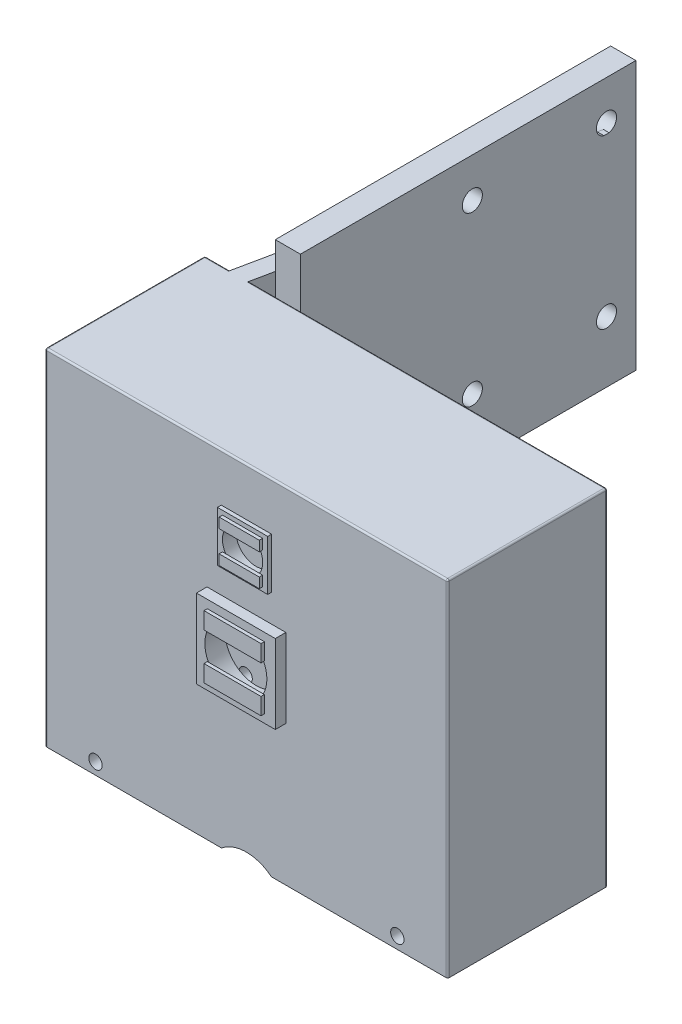
SolidWorks part; units mm, degrees
ref_plane "Front Plane" through (0, 0, 0) normal (0, 0, 1) x (1, 0, 0)
ref_plane "Top Plane" through (0, 0, 0) normal (0, 1, 0) x (1, 0, 0)
ref_plane "Right Plane" through (0, 0, 0) normal (1, 0, 0) x (0, 0, -1)
sketch "Sketch1" plane through (0, 0, 0) normal (1, 0, 0) x (0, 0, -1)
  line L1 (0, 0) -> (95.2, 0)
  line L2 (0, 0) -> (0, 205.7)
  line L3 (0, 205.7) -> (95.2, 205.7)
  line L4 (95.2, 0) -> (95.2, 205.7)
  dimension "D1" = 205.7
  dimension "D2" = 95.2
extrude "Boss-Extrude1" add sketch "Sketch1" against normal blind 240
sketch "Sketch2" plane through (0, 0, 0) normal (0, -1, 0) x (1, 0, 0)
  line L0 (0, 0) -> (0, -95.2) construction
  line L1 (-234.3, -5.7) -> (-5.7, -5.7)
  line L2 (-234.3, -5.7) -> (-234.3, -89.5)
  line L3 (-234.3, -89.5) -> (-5.7, -89.5)
  line L4 (-5.7, -5.7) -> (-5.7, -89.5)
  line L5 (-240, 0) -> (0, 0) construction
  line L6 (-240, 0) -> (-240, -95.2) construction
  line L7 (-240, -95.2) -> (0, -95.2) construction
  dimension "D1" = 5.7
  dimension "D2" = 5.7
  dimension "D3" = 5.7
  dimension "D4" = 5.7
extrude "Cut-Extrude1" cut sketch "Sketch2" against normal blind 194.3
fillet "Fillet1" radius 1 8 edges at (-240, 102.85, 0) (-240, 205.7, -47.6) (-240, 102.85, -95.2) (0, 102.85, -95.2) (-120, 205.7, -95.2) (-120, 205.7, 0) (0, 205.7, -47.6) (0, 102.85, 0)
sketch "Sketch3" plane through (0, 0, 0) normal (0, 0, 1) x (1, 0, 0)
  line L0 (-239, 0) -> (-1, 0) construction
  line L1 (0, 204.7) -> (0, 0) construction
  circle A0 centre (-120, 107) radius 18.5
  dimension "D1" = 107
  dimension "D2" = 120
  dimension "D3" = 37
extrude "Cut-Extrude2" cut sketch "Sketch3" against normal through all
sketch "Sketch4" plane through (0, 0, 0) normal (0, 0, 1) x (1, 0, 0)
  line L5 (-143.5, 130.5) -> (-96.5, 130.5)
  line L6 (-143.5, 130.5) -> (-143.5, 83.5)
  line L7 (-143.5, 83.5) -> (-96.5, 83.5)
  line L8 (-96.5, 130.5) -> (-96.5, 83.5)
  circle A0 centre (-120, 107) radius 18.5 construction
  dimension "D1" = 23.5
  dimension "D2" = 23.5
  dimension "D3" = 23.5
  dimension "D4" = 23.5
extrude "Boss-Extrude2" add sketch "Sketch4" along normal blind 6.3
sketch "Sketch6" plane through (0, 0, -95.2) normal (0, 0, -1) x (-1, 0, 0)
  line L1 (96.5, 130.5) -> (143.5, 130.5)
  line L2 (96.5, 130.5) -> (96.5, 83.5)
  line L3 (96.5, 83.5) -> (143.5, 83.5)
  line L4 (143.5, 130.5) -> (143.5, 83.5)
  circle A0 centre (120, 107) radius 18.5 construction
  circle A2 centre (120, 107) radius 18.5 construction
  dimension "D1" = 23.5
  dimension "D4" = 23.5
  dimension "D3" = 23.5
  dimension "D2" = 23.5
extrude "Boss-Extrude3" add sketch "Sketch6" along normal blind 6.3
sketch "Sketch7" plane through (0, 0, 0) normal (0, 0, 1) x (1, 0, 0)
  circle A0 centre (-120, 107) radius 18.5
  dimension "D3" = 37
extrude "Cut-Extrude3" cut sketch "Sketch7" against normal through all both and the other way through all
sketch "Sketch8" plane through (0, 0, 0) normal (0, 0, 1) x (1, 0, 0)
  line L6 (-239, 0) -> (-1, 0) construction
  circle A0 centre (-120, -18.2) radius 23.5
  dimension "D4" = 47
  dimension "D1" = 18.2
  dimension "D5" = 120
extrude "Cut-Extrude4" cut sketch "Sketch8" against normal through all both and the other way through all
sketch "Sketch9" plane through (0, 0, 0) normal (0, 0, 1) x (1, 0, 0)
  circle A0 centre (-120, 162) radius 12
  circle A1 centre (-120, 107) radius 18.5 construction
  point P4 (-120, 107)
  dimension "D1" = 55
  dimension "D2" = 24
extrude "Cut-Extrude5" cut sketch "Sketch9" against normal through all both and the other way through all
sketch "Sketch10" plane through (0, 0, 0) normal (0, 0, 1) x (1, 0, 0)
  line L1 (-135, 177) -> (-105, 177)
  line L2 (-135, 177) -> (-135, 147)
  line L3 (-135, 147) -> (-105, 147)
  line L4 (-105, 177) -> (-105, 147)
  circle A0 centre (-120, 162) radius 12 construction
  dimension "D2" = 15
  dimension "D3" = 15
  dimension "D4" = 15
  dimension "D1" = 15
extrude "Boss-Extrude5" add sketch "Sketch10" along normal blind 2.3
sketch "Sketch11" plane through (0, 0, -95.2) normal (0, 0, -1) x (-1, 0, 0)
  line L1 (105, 177) -> (135, 177)
  line L2 (105, 177) -> (105, 147)
  line L3 (105, 147) -> (135, 147)
  line L4 (135, 177) -> (135, 147)
  circle A0 centre (120, 162) radius 12 construction
  circle A1 centre (120, 162) radius 12 construction
  dimension "D1" = 15
  dimension "D2" = 15
  dimension "D3" = 15
  dimension "D4" = 15
extrude "Boss-Extrude6" add sketch "Sketch11" along normal blind 2.3
sketch "Sketch12" plane through (0, 0, 0) normal (0, 0, 1) x (1, 0, 0)
  circle A0 centre (-120, 162) radius 12
  point P4 (-120, 107)
  dimension "D2" = 24
extrude "Cut-Extrude6" cut sketch "Sketch12" against normal through all both and the other way through all
sketch "Sketch14" plane through (0, 0, 0) normal (0, 0, 1) x (1, 0, 0)
  line L0 (0, 204.7) -> (0, 0) construction
  line L1 (-239, 0) -> (-134.8664, 0) construction
  circle A0 centre (-30, 7) radius 4
  circle A1 centre (-210, 7) radius 4
  dimension "D3" = 8
  dimension "D4" = 8
  dimension "D5" = 7
  dimension "D1" = 180
  dimension "D2" = 30
extrude "Cut-Extrude7" cut sketch "Sketch14" against normal through all both
sketch "Sketch15" plane through (0, 0, -101.5) normal (0, 0, -1) x (-1, 0, 0)
  line L0 (96.5, 83.5) -> (143.5, 83.5) construction
  line L1 (103, 88.35) -> (137, 88.35)
  line L2 (103, 88.35) -> (103, 98.35)
  line L3 (103, 98.35) -> (137, 98.35)
  line L4 (137, 88.35) -> (137, 98.35)
  line L6 (103, 125.65) -> (137, 125.65)
  line L7 (103, 125.65) -> (103, 115.65)
  line L8 (103, 115.65) -> (137, 115.65)
  line L9 (137, 125.65) -> (137, 115.65)
  line L10 (143.5, 130.5) -> (96.5, 130.5) construction
  circle A0 centre (120, 107) radius 18.5 construction
  dimension "D1" = 4.85
  dimension "D2" = 34
  dimension "D3" = 17
  dimension "D4" = 10
  dimension "D5" = 34
  dimension "D6" = 17
  dimension "D7" = 10
  dimension "D8" = 4.85
extrude "Boss-Extrude7" add sketch "Sketch15" along normal blind 2
sketch "Sketch17" plane through (0, 0, 6.3) normal (0, 0, 1) x (1, 0, 0)
  line L0 (-143.5, 83.5) -> (-96.5, 83.5) construction
  line L1 (-137, 88.35) -> (-103, 88.35)
  line L2 (-137, 88.35) -> (-137, 98.35)
  line L3 (-137, 98.35) -> (-103, 98.35)
  line L4 (-103, 88.35) -> (-103, 98.35)
  line L5 (-96.5, 130.5) -> (-143.5, 130.5) construction
  line L6 (-137, 125.65) -> (-103, 125.65)
  line L7 (-137, 125.65) -> (-137, 115.65)
  line L8 (-137, 115.65) -> (-103, 115.65)
  line L9 (-103, 125.65) -> (-103, 115.65)
  circle A0 centre (-120, 107) radius 18.5 construction
  dimension "D1" = 4.85
  dimension "D2" = 34
  dimension "D3" = 17
  dimension "D4" = 10
  dimension "D5" = 34
  dimension "D6" = 17
  dimension "D7" = 10
  dimension "D8" = 4.85
extrude "Boss-Extrude14" add sketch "Sketch17" along normal blind 2
sketch "Sketch18" plane through (0, 0, 2.3) normal (0, 0, 1) x (1, 0, 0)
  line L0 (-135, 147) -> (-105, 147) construction
  line L1 (-132, 149.5) -> (-108, 149.5)
  line L2 (-132, 149.5) -> (-132, 155.5)
  line L3 (-132, 155.5) -> (-108, 155.5)
  line L4 (-108, 149.5) -> (-108, 155.5)
  line L5 (-105, 177) -> (-135, 177) construction
  line L6 (-132, 174.5) -> (-108, 174.5)
  line L7 (-132, 174.5) -> (-132, 168.5)
  line L8 (-132, 168.5) -> (-108, 168.5)
  line L9 (-108, 174.5) -> (-108, 168.5)
  circle A0 centre (-120, 162) radius 12 construction
  dimension "D1" = 12
  dimension "D2" = 24
  dimension "D3" = 2.5
  dimension "D4" = 6
  dimension "D5" = 24
  dimension "D6" = 12
  dimension "D7" = 6
  dimension "D8" = 2.5
extrude "Boss-Extrude17" add sketch "Sketch18" along normal blind 2
sketch "Sketch19" plane through (0, 0, -97.5) normal (0, 0, -1) x (-1, 0, 0)
  line L0 (135, 177) -> (105, 177) construction
  line L1 (108, 149.5) -> (132, 149.5)
  line L2 (108, 149.5) -> (108, 155.5)
  line L3 (108, 155.5) -> (132, 155.5)
  line L4 (132, 149.5) -> (132, 155.5)
  line L5 (132, 174.5) -> (108, 174.5)
  line L6 (132, 174.5) -> (132, 168.5)
  line L7 (132, 168.5) -> (108, 168.5)
  line L8 (108, 174.5) -> (108, 168.5)
  line L9 (105, 147) -> (135, 147) construction
  circle A0 centre (120, 162) radius 12 construction
  dimension "D1" = 2.5
  dimension "D2" = 2.5
  dimension "D3" = 24
  dimension "D4" = 12
  dimension "D5" = 6
  dimension "D6" = 12
  dimension "D7" = 24
  dimension "D8" = 6
extrude "Boss-Extrude18" add sketch "Sketch19" along normal blind 2
sketch "Sketch20" plane through (0, 0, -95.2) normal (0, 0, -1) x (-1, 0, 0)
  line L1 (183, 235) -> (198, 235)
  line L2 (183, 235) -> (183, 75)
  line L3 (183, 75) -> (198, 75)
  line L4 (198, 235) -> (198, 75)
  line L5 (0, 0) -> (0, 204.7) construction
  line L6 (239, 0) -> (134.8664, 0) construction
  dimension "D1" = 183
  dimension "D2" = 15
  dimension "D3" = 160
  dimension "D4" = 75
extrude "Boss-Extrude19" add sketch "Sketch20" along normal blind 200
sketch "Sketch21" plane through (-198, 0, 0) normal (-1, 0, 0) x (0, 0, 1)
  line L0 (-295.2, 75) -> (-295.2, 235) construction
  line L1 (-295.2, 235) -> (-95.2, 235) construction
  circle A0 centre (-277.7, 211.5) radius 6
  circle A1 centre (-197.7, 211.5) radius 6
  circle A2 centre (-277.7, 111.5) radius 6
  circle A3 centre (-197.7, 111.5) radius 6
  dimension "D1" = 12
  dimension "D2" = 12
  dimension "D3" = 12
  dimension "D4" = 12
  dimension "D9" = 23.5
  dimension "D5" = 80
  dimension "D6" = 80
  dimension "D7" = 100
  dimension "D8" = 17.5
extrude "Cut-Extrude8" cut sketch "Sketch21" against normal blind 20
sketch "Sketch22" plane through (0, 205.7, 0) normal (0, 1, 0) x (1, 0, 0)
  line L0 (-183, 295.2) -> (-225, 94.2)
  line L1 (-1, 94.2) -> (-239, 94.2) construction
  line L2 (-225, 94.2) -> (-213.7624, 94.2)
  line L3 (-213.7624, 94.2) -> (-183, 241.4202)
  line L4 (-183, 295.2) -> (-183, 95.2) construction
  line L5 (-183, 241.4202) -> (-183, 295.2)
  line L6 (-239, 94.2) -> (-239, 1) construction
  dimension "D1" = 11
  dimension "D2" = 14
extrude "Boss-Extrude20" add sketch "Sketch22" against normal blind 70
